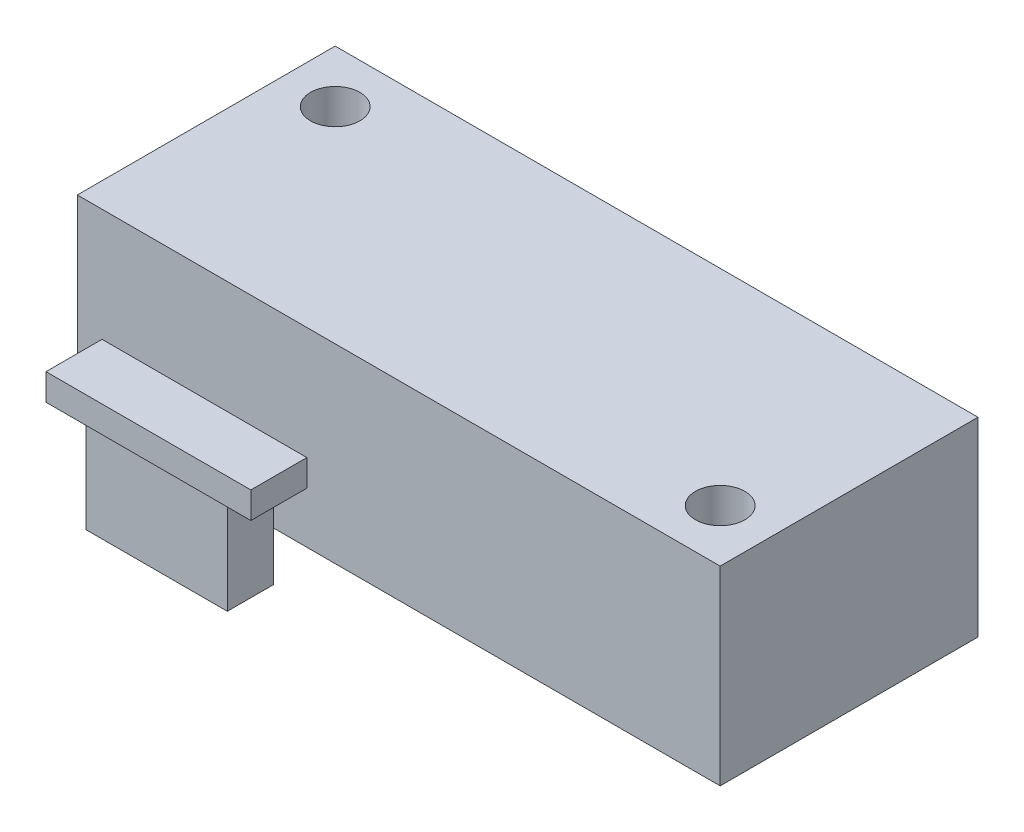
SolidWorks part; units mm, degrees
ref_plane "Front Plane" through (0, 0, 0) normal (0, 0, 1) x (1, 0, 0)
ref_plane "Top Plane" through (0, 0, 0) normal (0, 1, 0) x (1, 0, 0)
ref_plane "Right Plane" through (0, 0, 0) normal (1, 0, 0) x (0, 0, -1)
sketch "Sketch1" plane through (0, 0, 0) normal (0, 1, 0) x (1, 0, 0)
  line L1 (0, 0) -> (27.1018, 0)
  line L2 (0, 0) -> (0, 10.8712)
  line L3 (0, 10.8712) -> (27.1018, 10.8712)
  line L4 (27.1018, 0) -> (27.1018, 10.8712)
  line L5 (0, 0) -> (27.1018, 10.8712) construction
  line L6 (0, 10.8712) -> (27.1018, 0) construction
  circle A0 centre (2.2098, 8.6614) radius 1.0414
  circle A1 centre (24.892, 2.2098) radius 1.0414
  point P4 (13.5509, 5.4356)
  dimension "D3" = 2.0828
  dimension "D4" = 2.0828
  dimension "D6" = 2.2098
  dimension "D7" = 2.2098
  dimension "D1" = 10.8712
  dimension "D2" = 27.1018
  dimension "D5" = 2.2098
  dimension "D8" = 2.2098
extrude "Boss-Extrude4" add sketch "Sketch1" along normal blind 8.0264
ref_plane "Plane3" through (0, 2.159, 0) normal (0, -1, 0) x (-1, 0, 0)
sketch "Sketch5" plane through (0, 2.159, 0) normal (0, -1, 0) x (1, 0, 0)
  line L1 (1.0414, 0) -> (9.6774, 0)
  line L2 (1.0414, 0) -> (1.0414, 2.3622)
  line L3 (1.0414, 2.3622) -> (9.6774, 2.3622)
  line L4 (9.6774, 0) -> (9.6774, 2.3622)
  line L5 (1.0414, 0) -> (9.6774, 2.3622) construction
  line L6 (1.0414, 2.3622) -> (9.6774, 0) construction
  point P4 (5.3594, 1.1811)
  dimension "D2" = 8.636
  dimension "D3" = 2.3622
extrude "Boss-Extrude6" add sketch "Sketch5" against normal blind 1.1176
sketch "Sketch6" plane through (0, 2.159, 0) normal (0, -1, 0) x (1, 0, 0)
  line L0 (1.0414, 2.3622) -> (1.0414, 0) construction
  line L1 (2.3622, 2.0066) -> (8.3312, 2.0066)
  line L2 (2.3622, 2.0066) -> (2.3622, 0.0508)
  line L3 (2.3622, 0.0508) -> (8.3312, 0.0508)
  line L4 (8.3312, 2.0066) -> (8.3312, 0.0508)
  line L5 (2.3622, 2.0066) -> (8.3312, 0.0508) construction
  line L6 (2.3622, 0.0508) -> (8.3312, 2.0066) construction
  line L7 (9.6774, 2.3622) -> (1.0414, 2.3622) construction
  point P4 (5.3467, 1.0287)
  dimension "D1" = 5.969
  dimension "D2" = 1.9558
  dimension "D3" = 1.3208
  dimension "D4" = 0.3556
extrude "Boss-Extrude7" add sketch "Sketch6" along normal blind 4.1656
sketch "Sketch7" plane through (0, 0, 0) normal (0, -1, 0) x (1, 0, 0)
  text T0 "THIS PART\r\nDOWN\r\n" font "Century Gothic" height 2.54
extrude "Cut-Extrude1" cut sketch "Sketch7" against normal blind 2.286
